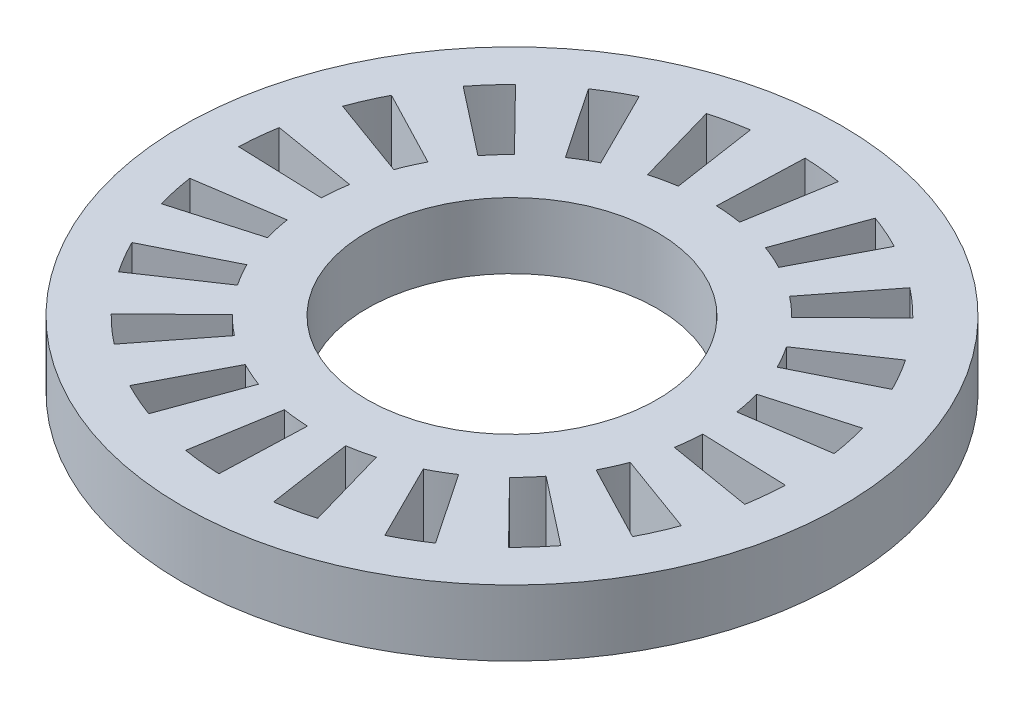
SolidWorks part; units mm, degrees
ref_plane "Front Plane" through (0, 0, 0) normal (0, 0, 1) x (1, 0, 0)
ref_plane "Top Plane" through (0, 0, 0) normal (0, 1, 0) x (1, 0, 0)
ref_plane "Right Plane" through (0, 0, 0) normal (1, 0, 0) x (0, 0, -1)
sketch "Sketch1" plane through (0, 0, 0) normal (0, 1, 0) x (1, 0, 0)
  line L0 (-10.2633, 3.7355) -> (0, 0) construction
  line L1 (-9.6879, 5.0432) -> (0, 0) construction
  line L2 (-9.6879, 5.0432) -> (-6.759, 3.5185)
  line L3 (-10.2633, 3.7355) -> (-7.1605, 2.6062)
  line L4 (0, 0) -> (0, 4.0303) construction
  line L5 (-8.6067, 6.7243) -> (-6.0046, 4.6913)
  line L6 (-7.6553, 7.7901) -> (-5.3409, 5.435)
  line L7 (-6.1075, 9.0547) -> (-4.261, 6.3173)
  line L8 (-4.8734, 9.7745) -> (-3.4, 6.8194)
  line L9 (-3.0105, 10.4989) -> (-2.1004, 7.3248)
  line L10 (-1.6144, 10.802) -> (-1.1263, 7.5363)
  line L11 (0.3812, 10.9153) -> (0.2659, 7.6154)
  line L12 (1.8026, 10.7722) -> (1.2577, 7.5155)
  line L13 (3.7355, 10.2633) -> (2.6062, 7.1605)
  line L14 (5.0432, 9.6879) -> (3.5185, 6.759)
  line L15 (6.7243, 8.6067) -> (4.6913, 6.0046)
  line L16 (7.7901, 7.6553) -> (5.435, 5.3409)
  line L17 (9.0547, 6.1075) -> (6.3173, 4.261)
  line L18 (9.7745, 4.8734) -> (6.8194, 3.4)
  line L19 (10.4989, 3.0105) -> (7.3248, 2.1004)
  line L20 (10.802, 1.6144) -> (7.5363, 1.1263)
  line L21 (10.9153, -0.3812) -> (7.6154, -0.2659)
  line L22 (10.7722, -1.8026) -> (7.5155, -1.2577)
  line L23 (10.2633, -3.7355) -> (7.1605, -2.6062)
  line L24 (9.6879, -5.0432) -> (6.759, -3.5185)
  line L25 (8.6067, -6.7243) -> (6.0046, -4.6913)
  line L26 (7.6553, -7.7901) -> (5.3409, -5.435)
  line L27 (6.1075, -9.0547) -> (4.261, -6.3173)
  line L28 (4.8734, -9.7745) -> (3.4, -6.8194)
  line L29 (3.0105, -10.4989) -> (2.1004, -7.3248)
  line L30 (1.6144, -10.802) -> (1.1263, -7.5363)
  line L31 (-0.3812, -10.9153) -> (-0.2659, -7.6154)
  line L32 (-1.8026, -10.7722) -> (-1.2577, -7.5155)
  line L33 (-3.7355, -10.2633) -> (-2.6062, -7.1605)
  line L34 (-5.0432, -9.6879) -> (-3.5185, -6.759)
  line L35 (-6.7243, -8.6067) -> (-4.6913, -6.0046)
  line L36 (-7.7901, -7.6553) -> (-5.435, -5.3409)
  line L37 (-9.0547, -6.1075) -> (-6.3173, -4.261)
  line L38 (-9.7745, -4.8734) -> (-6.8194, -3.4)
  line L39 (-10.4989, -3.0105) -> (-7.3248, -2.1004)
  line L40 (-10.802, -1.6144) -> (-7.5363, -1.1263)
  line L41 (-10.9153, 0.3812) -> (-7.6154, 0.2659)
  line L42 (-10.7722, 1.8026) -> (-7.5155, 1.2577)
  circle A0 centre (0, 0) radius 5.588
  circle A1 centre (0, 0) radius 12.7
  arc A2 (-9.6879, 5.0432) -> (-10.2633, 3.7355) centre (0, 0) ccw
  arc A3 (-6.759, 3.5185) -> (-7.1605, 2.6062) centre (0, 0) ccw
  arc A4 (-5.3409, 5.435) -> (-6.0046, 4.6913) centre (0, 0) ccw
  arc A5 (-7.6553, 7.7901) -> (-8.6067, 6.7243) centre (0, 0) ccw
  arc A6 (-3.4, 6.8194) -> (-4.261, 6.3173) centre (0, 0) ccw
  arc A7 (-4.8734, 9.7745) -> (-6.1075, 9.0547) centre (0, 0) ccw
  arc A8 (-1.1263, 7.5363) -> (-2.1004, 7.3248) centre (0, 0) ccw
  arc A9 (-1.6144, 10.802) -> (-3.0105, 10.4989) centre (0, 0) ccw
  arc A10 (1.2577, 7.5155) -> (0.2659, 7.6154) centre (0, 0) ccw
  arc A11 (1.8026, 10.7722) -> (0.3812, 10.9153) centre (0, 0) ccw
  arc A12 (3.5185, 6.759) -> (2.6062, 7.1605) centre (0, 0) ccw
  arc A13 (5.0432, 9.6879) -> (3.7355, 10.2633) centre (0, 0) ccw
  arc A14 (5.435, 5.3409) -> (4.6913, 6.0046) centre (0, 0) ccw
  arc A15 (7.7901, 7.6553) -> (6.7243, 8.6067) centre (0, 0) ccw
  arc A16 (6.8194, 3.4) -> (6.3173, 4.261) centre (0, 0) ccw
  arc A17 (9.7745, 4.8734) -> (9.0547, 6.1075) centre (0, 0) ccw
  arc A18 (7.5363, 1.1263) -> (7.3248, 2.1004) centre (0, 0) ccw
  arc A19 (10.802, 1.6144) -> (10.4989, 3.0105) centre (0, 0) ccw
  arc A20 (7.5155, -1.2577) -> (7.6154, -0.2659) centre (0, 0) ccw
  arc A21 (10.7722, -1.8026) -> (10.9153, -0.3812) centre (0, 0) ccw
  arc A22 (6.759, -3.5185) -> (7.1605, -2.6062) centre (0, 0) ccw
  arc A23 (9.6879, -5.0432) -> (10.2633, -3.7355) centre (0, 0) ccw
  arc A24 (5.3409, -5.435) -> (6.0046, -4.6913) centre (0, 0) ccw
  arc A25 (7.6553, -7.7901) -> (8.6067, -6.7243) centre (0, 0) ccw
  arc A26 (3.4, -6.8194) -> (4.261, -6.3173) centre (0, 0) ccw
  arc A27 (4.8734, -9.7745) -> (6.1075, -9.0547) centre (0, 0) ccw
  arc A28 (1.1263, -7.5363) -> (2.1004, -7.3248) centre (0, 0) ccw
  arc A29 (1.6144, -10.802) -> (3.0105, -10.4989) centre (0, 0) ccw
  arc A30 (-1.2577, -7.5155) -> (-0.2659, -7.6154) centre (0, 0) ccw
  arc A31 (-1.8026, -10.7722) -> (-0.3812, -10.9153) centre (0, 0) ccw
  arc A32 (-3.5185, -6.759) -> (-2.6062, -7.1605) centre (0, 0) ccw
  arc A33 (-5.0432, -9.6879) -> (-3.7355, -10.2633) centre (0, 0) ccw
  arc A34 (-5.435, -5.3409) -> (-4.6913, -6.0046) centre (0, 0) ccw
  arc A35 (-7.7901, -7.6553) -> (-6.7243, -8.6067) centre (0, 0) ccw
  arc A36 (-6.8194, -3.4) -> (-6.3173, -4.261) centre (0, 0) ccw
  arc A37 (-9.7745, -4.8734) -> (-9.0547, -6.1075) centre (0, 0) ccw
  arc A38 (-7.5363, -1.1263) -> (-7.3248, -2.1004) centre (0, 0) ccw
  arc A39 (-10.802, -1.6144) -> (-10.4989, -3.0105) centre (0, 0) ccw
  arc A40 (-7.5155, 1.2577) -> (-7.6154, 0.2659) centre (0, 0) ccw
  arc A41 (-10.7722, 1.8026) -> (-10.9153, 0.3812) centre (0, 0) ccw
  point P88 (0, 0)
  point P113 (0, 0)
  dimension "D1" = 11.176
  dimension "D2" = 25.4
  dimension "D4" = 7.62
  dimension "D5" = 10.922
  dimension "D6" = 7.5
  dimension "D3" = 20
  dimension "D7" = 70
extrude "Boss-Extrude1" add sketch "Sketch1" along normal blind 2.54
